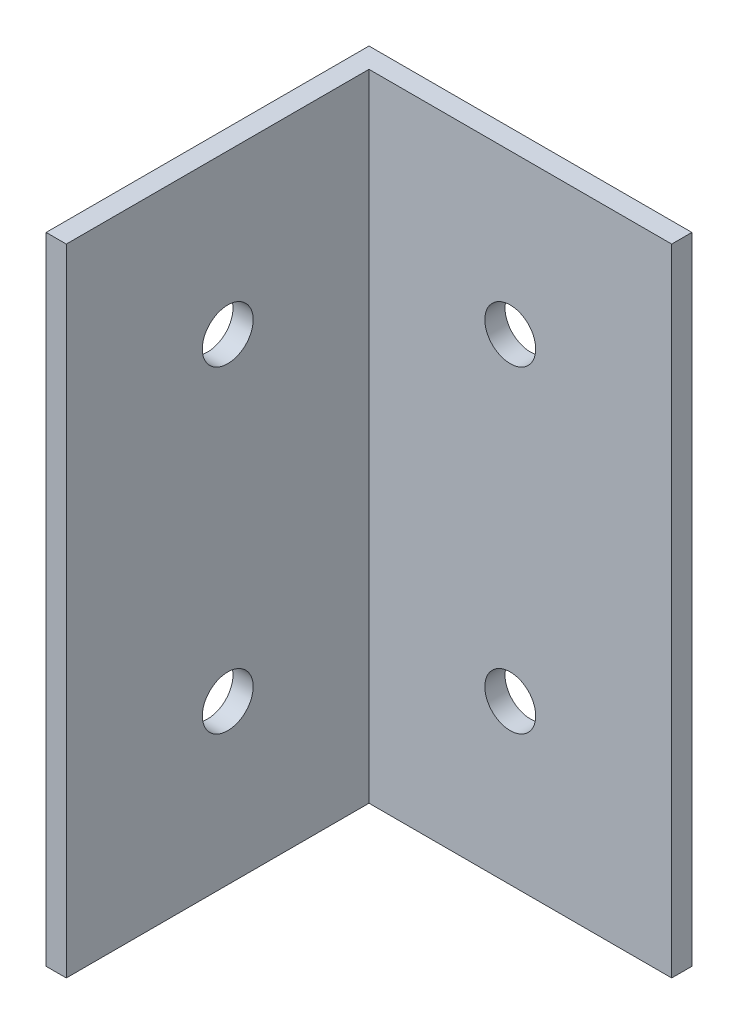
SolidWorks part; units mm, degrees
ref_plane "Front Plane" through (0, 0, 0) normal (0, 0, 1) x (1, 0, 0)
ref_plane "Top Plane" through (0, 0, 0) normal (0, 1, 0) x (1, 0, 0)
ref_plane "Right Plane" through (0, 0, 0) normal (1, 0, 0) x (0, 0, -1)
sketch "Sketch1" plane through (0, 0, 0) normal (0, 1, 0) x (1, 0, 0)
  line L0 (0, 0) -> (0, -50.8)
  line L1 (0, -50.8) -> (3.175, -50.8)
  line L2 (3.175, -50.8) -> (3.175, -3.175)
  line L3 (3.175, -3.175) -> (50.8, -3.175)
  line L4 (50.8, -3.175) -> (50.8, 0)
  line L5 (50.8, 0) -> (0, 0)
  dimension "D1" = 50.8
  dimension "D2" = 50.8
  dimension "D3" = 3.175
  dimension "D4" = 3.175
extrude "Boss-Extrude1" add sketch "Sketch1" along normal blind 100
sketch "Sketch2" plane through (0, 0, 0) normal (0, 0, -1) x (-1, 0, 0)
  line L0 (-50.8, 50) -> (0, 50) construction
  line L1 (-50.8, 100) -> (-50.8, 0) construction
  line L2 (0, 100) -> (0, 0) construction
  line L3 (-25.4, 50) -> (-25.4, 100) construction
  line L4 (-50.8, 100) -> (0, 100) construction
  line L5 (-25.4, 50) -> (-25.4, 0) construction
  line L6 (-50.8, 0) -> (0, 0) construction
  circle A0 centre (-25.4, 75) radius 4
  circle A1 centre (-25.4, 25) radius 4
  dimension "D1" = 8
extrude "Cut-Extrude1" cut sketch "Sketch2" against normal up to next
ref_plane "Plane1" through (0, 0, 0) normal (0.7071, 0, -0.7071) x (-0.7071, 0, -0.7071)
mirror "Mirror1" about plane through (0, 0, 0) normal (0.7071, 0, -0.7071) of "Cut-Extrude1"
